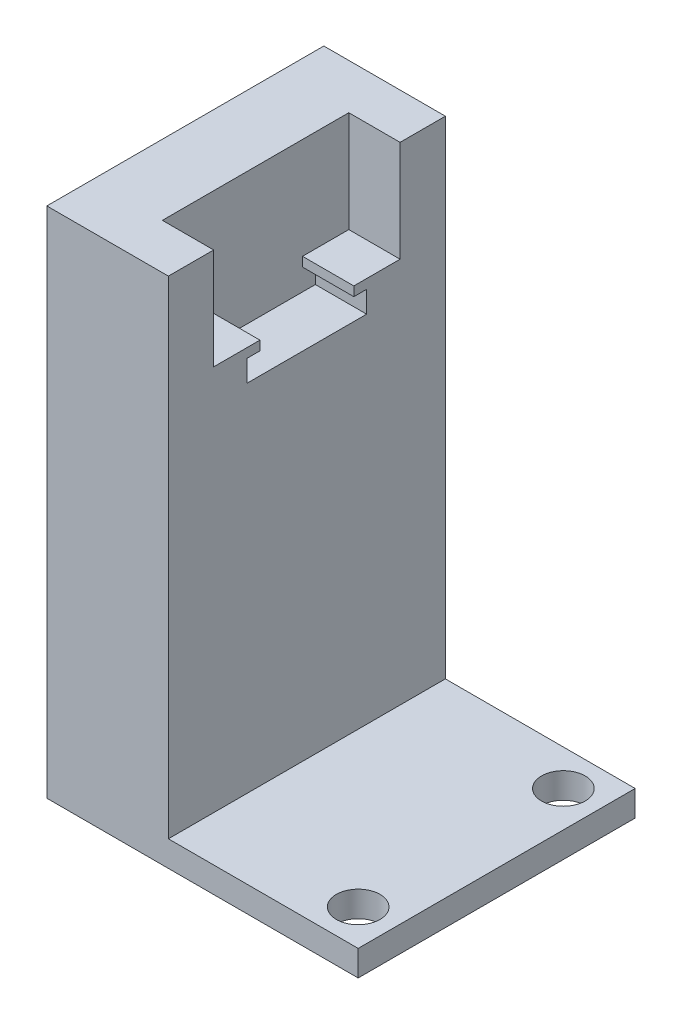
SolidWorks part; units mm, degrees
ref_plane "Front Plane" through (0, 0, 0) normal (0, 0, 1) x (1, 0, 0)
ref_plane "Top Plane" through (0, 0, 0) normal (0, 1, 0) x (1, 0, 0)
ref_plane "Right Plane" through (0, 0, 0) normal (1, 0, 0) x (0, 0, -1)
sketch "Sketch1" plane through (0, 0, 0) normal (0, 1, 0) x (1, 0, 0)
  line L0 (35.195, -20) -> (35.195, 0) construction
  line L1 (-42.195, -27) -> (42.195, -27)
  line L2 (-42.195, -27) -> (-42.195, 27)
  line L3 (-42.195, 27) -> (42.195, 27)
  line L4 (42.195, -27) -> (42.195, 27)
  line L5 (-42.195, -27) -> (42.195, 27) construction
  line L6 (-42.195, 27) -> (42.195, -27) construction
  line L7 (35.195, 0) -> (0, 0) construction
  line L8 (35.195, 0) -> (35.195, 20) construction
  line L9 (35.195, 20) -> (35.195, 27) construction
  line L10 (35.195, -20) -> (35.195, -27) construction
  circle A0 centre (35.195, 20) radius 4.25
  circle A1 centre (35.195, -20) radius 4.25
  point P0 (0, 0)
  dimension "D1" = 8.5
  dimension "D2" = 40
  dimension "D3" = 7
  dimension "D4" = 7
  dimension "D5" = 84.39
extrude "Boss-Extrude1" add sketch "Sketch1" along normal blind 100
sketch "Sketch2" plane through (-42.195, 0, 0) normal (-1, 0, 0) x (0, 0, 1)
  line L0 (-11.65, 78.45) -> (-9.15, 78.45)
  line L1 (-27, 100) -> (27, 100) construction
  line L6 (-18.1714, 100) -> (0, 100)
  line L7 (0, 100) -> (0, 74.25)
  line L8 (0, 74.25) -> (-11.65, 74.25)
  line L9 (-11.65, 74.25) -> (-11.65, 78.45)
  line L11 (-27, 0) -> (27, 0) construction
  line L12 (-9.15, 78.45) -> (-9.15, 80.2676)
  line L13 (-9.15, 80.2676) -> (-18.1714, 80.2676)
  line L14 (-18.1714, 80.2676) -> (-18.1714, 100)
  point P0 (0, 100)
  dimension "D1" = 4.2
  dimension "D2" = 2.5
  dimension "D3" = 11.65
  dimension "D4" = 74.25
extrude "Cut-Extrude1" cut sketch "Sketch2" against normal blind 10
sketch "Sketch3" plane through (0, 100, 0) normal (0, 1, 0) x (1, 0, 0)
  line L0 (-42.195, -27) -> (42.195, -27) construction
  line L1 (42.195, 27) -> (5.1956, 27)
  line L2 (42.195, 27) -> (42.195, -27)
  line L3 (42.195, -27) -> (5.1956, -27)
  line L4 (5.1956, 27) -> (5.1956, -27)
extrude "Cut-Extrude2" cut sketch "Sketch3" against normal offset from surface (95 mm away) 5 up to face at (35.195, 0, -15.75)
mirror "Mirror1" about plane through (0, 0, 0) normal (0, 0, 1) of "Cut-Extrude1"
ref_plane "Plane1" through (-18.4997, 0, 0) normal (1, 0, 0) x (0, 0, -1)
mirror "Mirror2" about plane through (-18.4997, 0, 0) normal (1, 0, 0) of "Mirror1", "Cut-Extrude1"
sketch "Sketch4" plane through (-18.4997, 0, 0) normal (1, 0, 0) x (0, 0, -1)
  line L1 (-48.1799, 115.246) -> (93.2252, 115.246)
  line L2 (-48.1799, 115.246) -> (-48.1799, -25.9269)
  line L3 (-48.1799, -25.9269) -> (93.2252, -25.9269)
  line L4 (93.2252, 115.246) -> (93.2252, -25.9269)
  point P4 (93.2252, -25.9269)
extrude "Cut-Extrude3" cut sketch "Sketch4" against normal up to next
